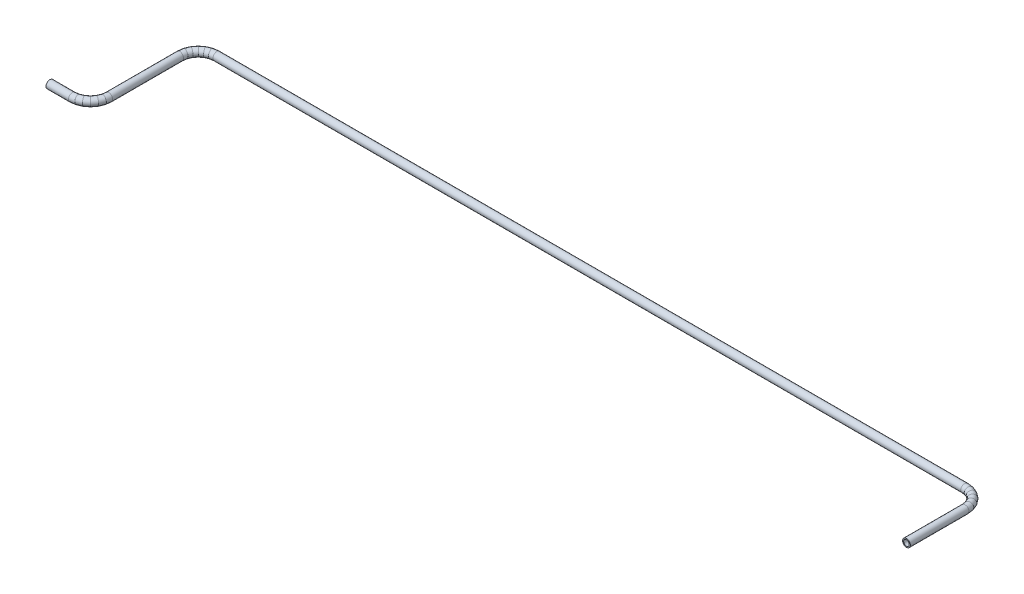
SolidWorks part; units mm, degrees
ref_plane "Front Plane" through (0, 0, 0) normal (0, 0, 1) x (1, 0, 0)
ref_plane "Top Plane" through (0, 0, 0) normal (0, 1, 0) x (1, 0, 0)
ref_plane "Right Plane" through (0, 0, 0) normal (1, 0, 0) x (0, 0, -1)
sketch3d "Path"
  line L0 (-3585.8928, 0, 0) -> (-3567.6928, 0, 0)
  line L1 (-3567.6928, 0, 0) -> (-3563.8105, 0, -0.5111)
  line L2 (-3563.8105, 0, -0.5111) -> (-3560.1928, 0, -2.0096)
  line L3 (-3560.1928, 0, -2.0096) -> (-3557.0862, 0, -4.3934)
  line L4 (-3557.0862, 0, -4.3934) -> (-3554.7024, 0, -7.5)
  line L5 (-3554.7024, 0, -7.5) -> (-3553.2039, 0, -11.1177)
  line L6 (-3553.2039, 0, -11.1177) -> (-3552.6928, 0, -15)
  line L7 (-3552.6928, 0, -15) -> (-3552.6928, 0, -73)
  line L8 (-3552.6928, 0, -73) -> (-3552.1817, 0, -76.8823)
  line L9 (-3552.1817, 0, -76.8823) -> (-3550.6832, 0, -80.5)
  line L10 (-3550.6832, 0, -80.5) -> (-3548.2994, 0, -83.6066)
  line L11 (-3548.2994, 0, -83.6066) -> (-3545.1928, 0, -85.9904)
  line L12 (-3545.1928, 0, -85.9904) -> (-3541.5751, 0, -87.4889)
  line L13 (-3541.5751, 0, -87.4889) -> (-3537.6928, 0, -88)
  line L14 (-3537.6928, 0, -88) -> (-2926.5928, 0, -88)
  line L15 (-2926.5928, 0, -88) -> (-2922.7105, 0, -87.4889)
  line L16 (-2922.7105, 0, -87.4889) -> (-2919.0928, 0, -85.9904)
  line L17 (-2919.0928, 0, -85.9904) -> (-2915.9862, 0, -83.6066)
  line L18 (-2915.9862, 0, -83.6066) -> (-2913.6024, 0, -80.5)
  line L19 (-2913.6024, 0, -80.5) -> (-2912.1039, 0, -76.8823)
  line L20 (-2912.1039, 0, -76.8823) -> (-2911.5928, 0, -73)
  line L21 (-2911.5928, 0, -73) -> (-2911.5928, 0, -25.3)
ref_plane "Start Plane" through (-3585.8928, 0, 0) normal (1, 0, 0) x (0, 0, -1)
sketch "Profile" plane through (-3585.8928, 0, 0) normal (1, 0, 0) x (0, 0, -1)
  circle A0 centre (0, 0) radius 3.175
  circle A1 centre (0, 0) radius 2.286
sweep "Tube" add profiles "Profile" path "Path"
